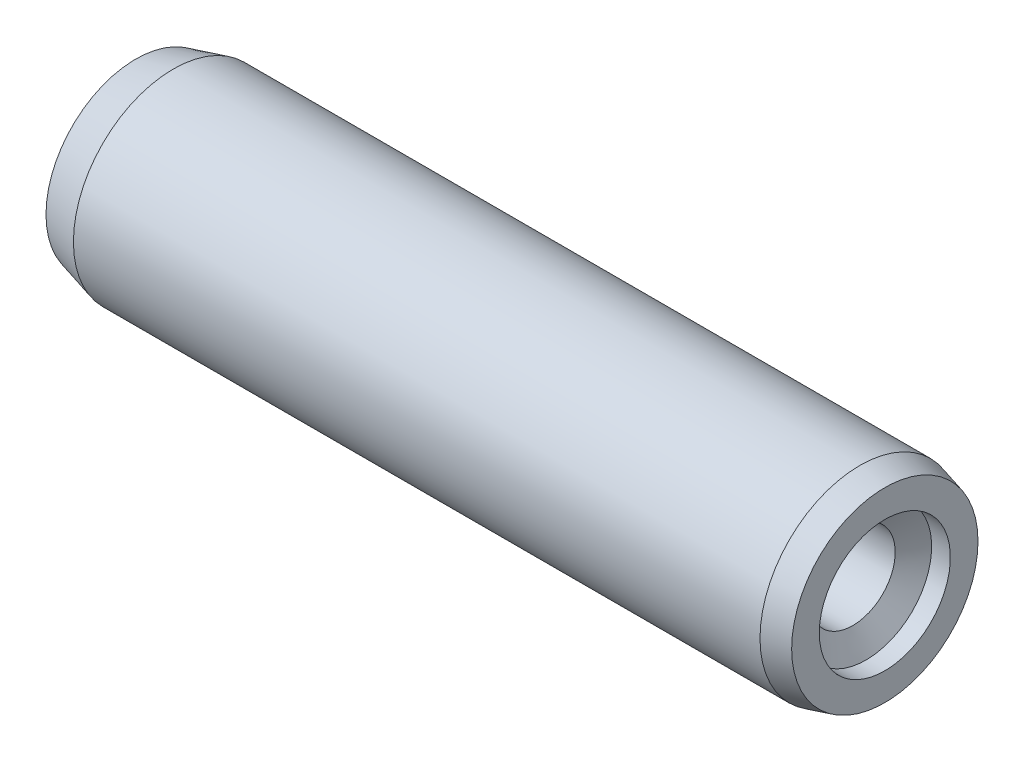
SolidWorks part; units mm, degrees
revolve "Body" add sketch "BodySke" angle 360 about L0
sketch "BodySke" plane through (0, 0, 0) normal (0, 0, 1) x (1, 0, 0)
  line L0 (0, 0) -> (66, 0) construction
  line L1 (0, 0) -> (40, 0) construction
  line L2 (3, 8) -> (58, 8)
  line L3 (58, 8) -> (60, 7.4641)
  line L4 (0, 0) -> (33.5917, 0)
  line L5 (60, 7.4641) -> (60, 5.25)
  line L6 (60, 5.25) -> (58.5, 5.25)
  line L7 (58.5, 5.25) -> (57.4319, 3.4)
  line L8 (57.4319, 3.4) -> (35, 3.4)
  line L9 (35, 3.4) -> (33.5917, 0)
  line L10 (57.25, 7) -> (57.25, 3) construction
  line L11 (44, 16) -> (44, 0) construction
  line L12 (3, 8) -> (0, 7.1962)
  line L13 (0, 0) -> (0, 7.1962)
  dimension "D1" = 75
  dimension "Head_ch_len" = 2
  dimension "Cbore_dia" = 10.5
  dimension "Cbore_dep" = 1.5
  dimension "Tapdrill_dia" = 6.8
  dimension "Tapdrill_dep" = 25
  dimension "D3" = 67.5
  dimension "Length" = 60
  dimension "D4" = 30
  dimension "Advance" = 1.25
  dimension "Thread_dep" = 16
  dimension "Diameter" = 16
  dimension "D2" = 165
  dimension "Tip_ch_len" = 3
cosmetic thread "ThreadCosmetic" [suppressed]
ref_plane "Plane1" through (0, 0, 0) normal (0, 0, 1) x (1, 0, 0)
ref_plane "Plane2" through (0, 0, 0) normal (0, 1, 0) x (1, 0, 0)
ref_plane "Plane3" through (0, 0, 0) normal (1, 0, 0) x (0, 0, -1)
sketch "ThdSchSke" plane through (0, 0, 0) normal (0, 0, 1) x (1, 0, 0)
  line L0 (57.7783, 4) -> (58.2618, 3.3095)
  line L2 (57.7783, 4) -> (57.2948, 3.3095)
  line L3 (57.2948, 3.3095) -> (58.2618, 3.3095)
  line L4 (57.7783, 5.8566) -> (57.7783, 1.7596) construction
  line L5 (27, 0) -> (36, 0) construction
  line L6 (0, 0) -> (66, 0) construction
  line L7 (60, -7.4641) -> (60, 7.4641) construction
  dimension "D1" = 70
revolve "ThreadSchematic" [suppressed] cut sketch "ThdSchSke" angle 360 about L5
pattern_linear "ThdSchPat" [suppressed]
equation "' \"Diameter@BodySke\" = 16"
equation "' \"Head_ch_len@BodySke\" = 2"
equation "' \"Tip_ch_len@BodySke\" = 3"
equation "' \"Thread_major@ThreadCosmetic\"  = 8"
equation "' \"Thread_major@ThreadCosmetic\" = 8"
equation "' \"Advance@BodySke\" = 1.25"
equation "' \"Cbore_dia@BodySke\" = 10.5"
equation "' \"Thread_dep@BodySke\"  = 16"
equation "' \"Thread_dep@BodySke\" = 16"
equation "' \"Tapdrill_dep@BodySke\" = 25"
equation "' \"Cbore_dep@BodySke\" = 1.5"
equation "' \"Tapdrill_dia@BodySke\" = 6.8"
equation "' \"Thread_minor@ThdSchSke\" = 6.619"
equation "'  \"Length@BodySke\" = 60"
equation "' \"Diameter@BodySke\" = 30"
equation "' \"Head_ch_len@BodySke\" = 4"
equation "' \"Tip_ch_len@BodySke\" = 5"
equation "' \"Thread_major@ThreadCosmetic\"  = 20"
equation "' \"Thread_major@ThreadCosmetic\" = 20"
equation "' \"Advance@BodySke\" = 2.5"
equation "' \"Cbore_dia@BodySke\" = 21"
equation "' \"Thread_dep@BodySke\"  = 30"
equation "' \"Thread_dep@BodySke\" = 30"
equation "' \"Tapdrill_dep@BodySke\" = 40"
equation "' \"Cbore_dep@BodySke\" = 2"
equation "' \"Tapdrill_dia@BodySke\" = 17.5"
equation "' \"Thread_minor@ThdSchSke\" = 17.252"
equation "\"Depth@ThreadCosmetic\" = \"Thread_dep@BodySke\"  -  \"Cbore_dep@BodySke\""
equation "\"Thread_nominal@ThdSchSke\" = \"Thread_major@ThreadCosmetic\""
equation "\"Inset@ThdSchSke\" = \"Cbore_dep@BodySke\" + (\"Cbore_dia@BodySke\" - \"Thread_major@ThreadCosmetic\") / 2 * tan(30 * 0.0174533)"
equation "\"Num_threads@ThdSchPat\" = int(  ( \"Thread_dep@BodySke\"  - \"Inset@ThdSchSke\" ) / \"Advance@BodySke\" + 0.999 )  + 1"
equation "\"Advance@ThdSchPat\" = (  \"Thread_dep@BodySke\" - \"Inset@ThdSchSke\" ) /  (\"Num_threads@ThdSchPat\" - 1) 'relax it"
